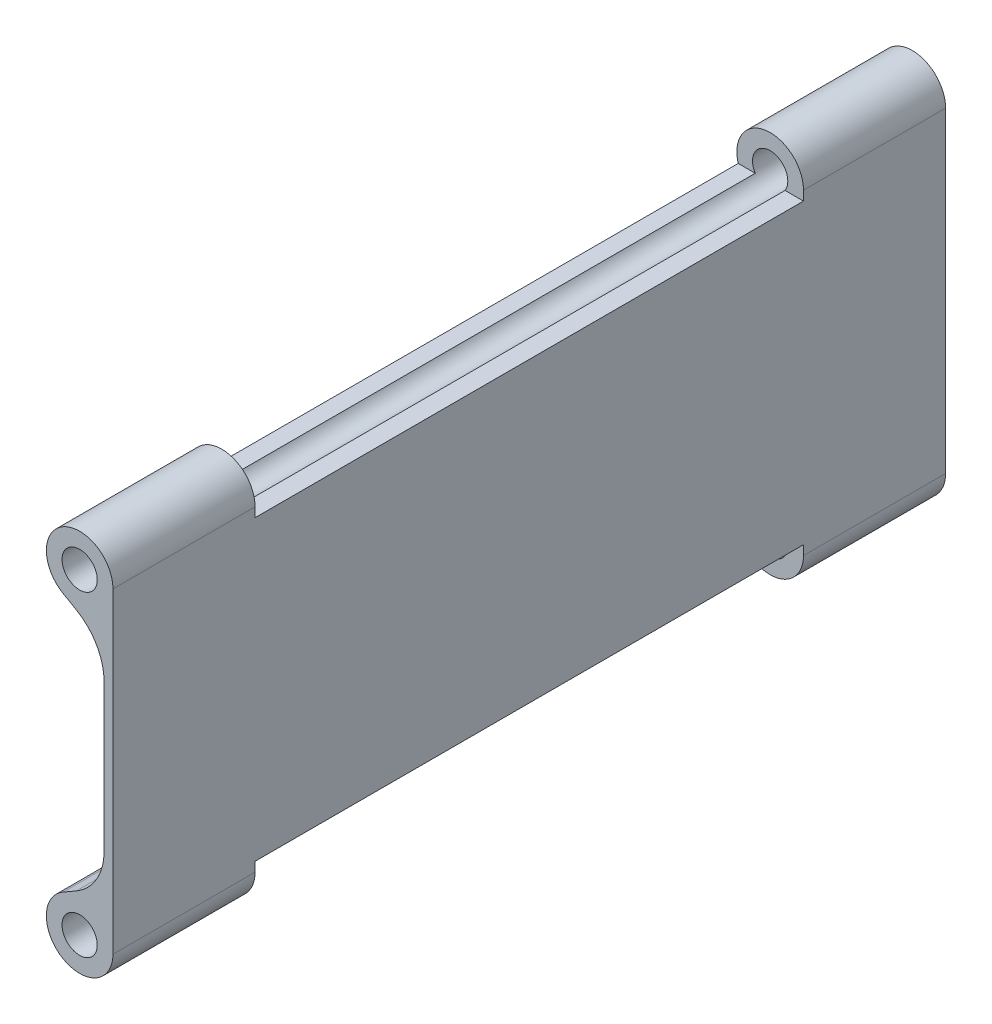
SolidWorks part; units mm, degrees
material "ABS"
ref_plane "Alzado" through (0, 0, 0) normal (0, 0, 1) x (1, 0, 0)
ref_plane "Planta" through (0, 0, 0) normal (0, 1, 0) x (1, 0, 0)
ref_plane "Vista lateral" through (0, 0, 0) normal (1, 0, 0) x (0, 0, -1)
sketch "Croquis1" plane through (0, 0, 0) normal (0, 0, 1) x (1, 0, 0)
  line L5 (-13.465, 0) -> (13.8234, 0) construction
  line L8 (-1.6, 19.0562) -> (-8.9869, 23.2963)
  line L9 (-1.6, 19.0562) -> (-1.6, -19.0562)
  line L10 (0, 28.5) -> (0, -28.5)
  line L11 (-1.6, -19.0562) -> (-8.9869, -23.2963)
  circle A0 centre (-6, 28.5) radius 3.175
  arc A5 (0, 28.5) -> (-8.9869, 23.2963) centre (-6, 28.5) ccw
  arc A6 (0, -28.5) -> (-8.9869, -23.2963) centre (-6, -28.5) cw
  circle A7 centre (-6, -28.5) radius 3.175
  point P7 (0, 0)
  point P15 (0, 0)
  point P16 (-1.6, 0)
  point P17 (-1.6, 0)
  dimension "D1" = 6.35
  dimension "D2" = 57
  dimension "D3" = 1.6
  dimension "D4" = 6
extrude "Saliente-Extruir1" add sketch "Croquis1" against normal blind 150
fillet "Redondeo1" radius 10 2 edges at (-1.6, -19.0562, -75) (-1.6, 19.0562, -75)
sketch "Croquis3" plane through (0, 0, 0) normal (1, 0, 0) x (0, 0, -1)
  line L0 (0, 0) -> (150, 0) construction
  line L1 (25.6041, 44.9478) -> (124.3959, 44.9478)
  line L2 (25.6041, 44.9478) -> (25.6041, 26.8024)
  line L3 (25.6041, 26.8024) -> (124.3959, 26.8024)
  line L4 (124.3959, 44.9478) -> (124.3959, 26.8024)
  line L5 (124.3959, -44.9478) -> (124.3959, -26.8024)
  line L6 (25.6041, -26.8024) -> (124.3959, -26.8024)
  line L7 (25.6041, -44.9478) -> (25.6041, -26.8024)
  line L8 (25.6041, -44.9478) -> (124.3959, -44.9478)
  line L9 (150, 13.2659) -> (150, -13.2659) construction
  point P16 (75, 0)
  point P17 (75, -26.8024)
extrude "Cortar-Extruir2" cut sketch "Croquis3" against normal through all
